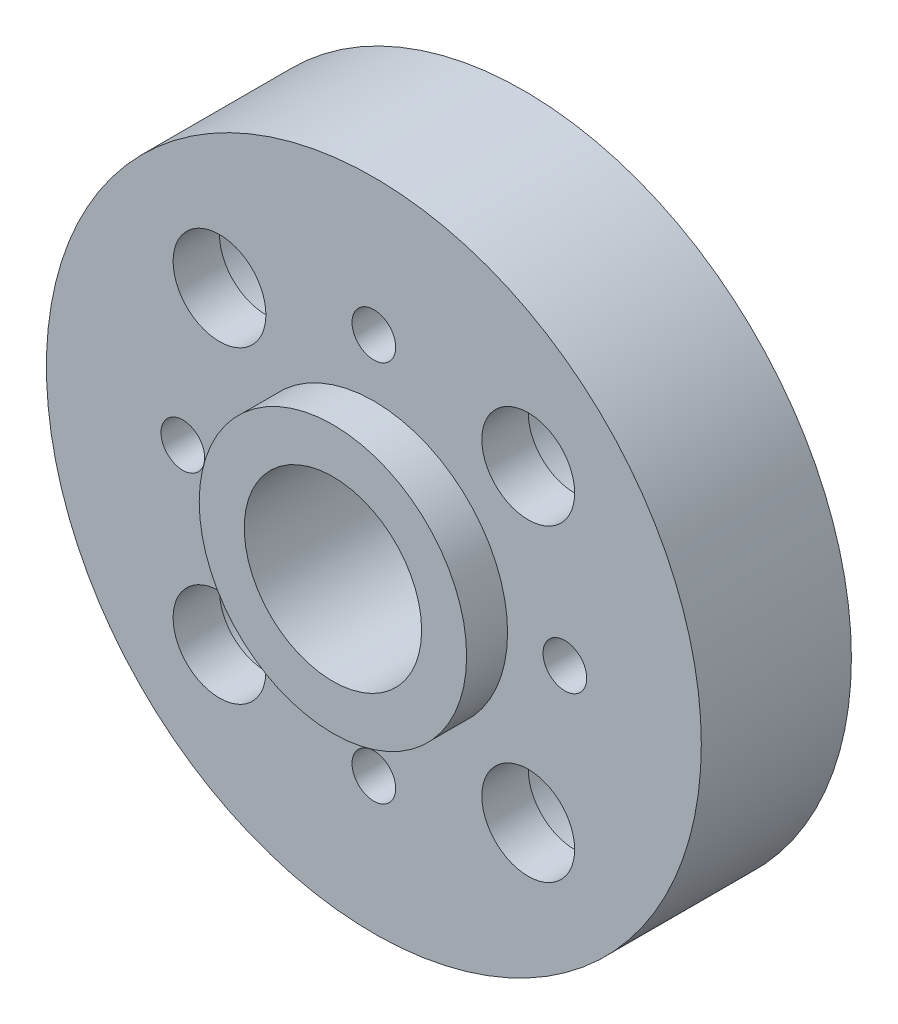
SolidWorks part; units mm, degrees
ref_plane "前视基准面" through (0, 0, 0) normal (0, 0, 1) x (1, 0, 0)
ref_plane "上视基准面" through (0, 0, 0) normal (0, 1, 0) x (1, 0, 0)
ref_plane "右视基准面" through (0, 0, 0) normal (1, 0, 0) x (0, 0, -1)
other "Configuration Table"
sketch "转接板_D24_厚5.5_工具通孔D6.5_截面" plane through (0, 0, 0) normal (0, 0, 1) x (1, 0, 0)
  circle A0 centre (0, 0) radius 12
  circle A1 centre (0, 0) radius 3.25
  dimension "D1" = 24
  dimension "D2" = 6.5
extrude "转接板_D24_厚5.5_工具通孔D6.5" add sketch "转接板_D24_厚5.5_工具通孔D6.5_截面" along normal blind 5.5
sketch "轴承内孔定位台_D9.8_高1.5_截面" plane through (0, 0, 0) normal (0, 0, 1) x (1, 0, 0)
  circle A0 centre (0, 0) radius 4.9
  circle A1 centre (0, 0) radius 3.25
  dimension "D1" = 9.8
  dimension "D2" = 6.5
extrude "轴承内孔定位台_D9.8_高1.5" add sketch "轴承内孔定位台_D9.8_高1.5_截面" along normal blind 1.5 from offset 5.5
sketch "轴承内圈孔位_PCD16_错开45度" plane through (0, 0, 0) normal (0, 0, -1) x (-1, 0, 0)
  point P0 (-5.6569, 5.6569)
  point P1 (5.6569, 5.6569)
  point P2 (5.6569, -5.6569)
  point P3 (-5.6569, -5.6569)
hole_wizard "轴承内圈_4xD3.4通孔_D5.8沉孔_PCD16" positions "3D草图1" profile "草图4" counterbore size "M3" standard "ISO" end condition through all
sketch3d "3D草图1"
  point P0 (5.6569, -5.6569, 0)
  point P2 (-5.6569, -5.6569, 0)
  point P4 (-5.6569, 5.6569, 0)
  point P6 (5.6569, 5.6569, 0)
sketch "草图4" plane through (5.6569, -5.6569, 0) normal (1, 0, 0) x (0, 1, 0)
  line L0 (0, 0) -> (0, 7)
  line L1 (0, 7) -> (1.7, 7)
  line L3 (1.7, 7) -> (1.7, 3.8)
  line L4 (1.7, 3.8) -> (2.9, 3.8)
  line L5 (2.9, 3.8) -> (2.9, 0)
  line L7 (2.9, 0) -> (0, 0)
  line L11 (0, -6.35) -> (0, 107.95) construction
  dimension "通孔孔直径" = 3.4
  dimension "通孔孔深度" = 7
  dimension "柱形沉头孔直径" = 5.8
  dimension "柱形沉头孔深度" = 3.8
sketch "舵盘止口_截面" plane through (0, 0, 0) normal (0, 0, 1) x (1, 0, 0)
  circle A0 centre (0, 0) radius 10.05
  dimension "D1" = 20.1
extrude "原舵盘定位槽_D20.1_深0.6" cut sketch "舵盘止口_截面" along normal blind 0.6
sketch "原舵盘孔位_PCD14" plane through (0, 0, 0.6) normal (0, 0, -1) x (-1, 0, 0)
  point P0 (-7, 0)
  point P1 (0, 7)
  point P2 (7, 0)
  point P3 (0, -7)
hole_wizard "原舵盘_4xM2x0.4通螺纹_PCD14" positions "3D草图2" profile "草图7" tap size "M2" standard "ISO" end condition through all
sketch3d "3D草图2"
  point P0 (0, -7, 0.6)
  point P2 (-7, 0, 0.6)
  point P4 (0, 7, 0.6)
  point P6 (7, 0, 0.6)
sketch "草图7" plane through (0, -7, 0.6) normal (1, 0, 0) x (0, 1, 0)
  line L0 (0, 0) -> (0, 6.4)
  line L1 (0, 6.4) -> (0.8, 6.4)
  line L2 (0.8, 6.4) -> (0.8, 0)
  line L5 (0.8, 0) -> (0, 0)
  line L11 (0, -6.35) -> (0, 107.95) construction
  dimension "通孔螺纹孔钻头直径" = 1.6
  dimension "通孔螺纹孔钻头深度" = 6.4
cosmetic thread "孔螺纹线1" parameters "D2"=2
cosmetic thread "孔螺纹线2" parameters "D2"=2
cosmetic thread "孔螺纹线3" parameters "D2"=2
cosmetic thread "孔螺纹线4" parameters "D2"=2
